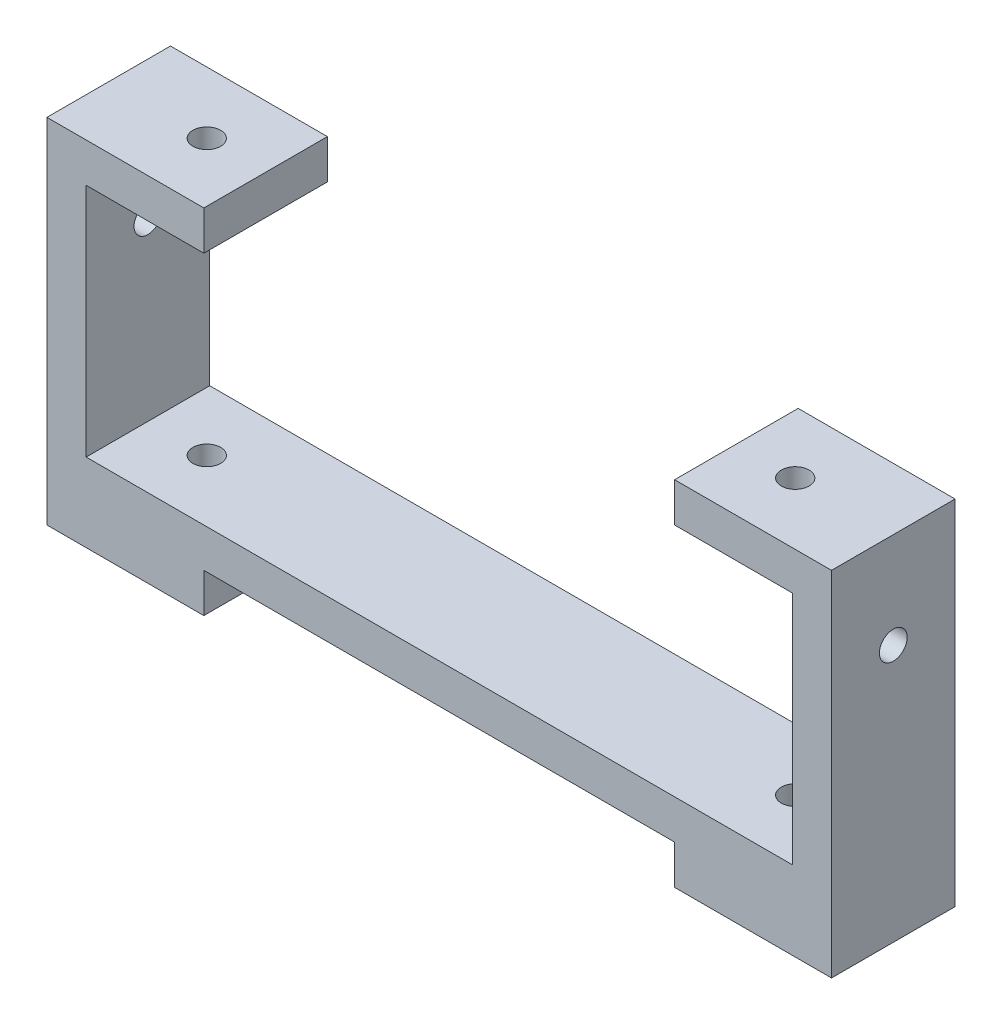
SolidWorks part; units mm, degrees
ref_plane "Front Plane" through (0, 0, 0) normal (0, 0, 1) x (1, 0, 0)
ref_plane "Top Plane" through (0, 0, 0) normal (0, 1, 0) x (1, 0, 0)
ref_plane "Right Plane" through (0, 0, 0) normal (1, 0, 0) x (0, 0, -1)
sketch "Sketch1" plane through (0, 0, 0) normal (0, 0, 1) x (1, 0, 0)
  line L0 (-57.15, -1.651) -> (-57.15, 36.449)
  line L1 (38.1, -8.001) -> (-38.1, -8.001)
  line L3 (-57.15, -1.651) -> (57.15, -1.651)
  line L7 (-57.15, 36.449) -> (-38.1, 36.449)
  line L8 (-38.1, 36.449) -> (-38.1, 42.799)
  line L9 (-38.1, 42.799) -> (-63.5, 42.799)
  line L10 (-63.5, 42.799) -> (-63.5, -3.175)
  line L12 (0, 0) -> (0, 14.3553) construction
  line L14 (63.5, 42.799) -> (63.5, -3.175)
  line L15 (38.1, 42.799) -> (63.5, 42.799)
  line L16 (38.1, 36.449) -> (38.1, 42.799)
  line L17 (57.15, 36.449) -> (38.1, 36.449)
  line L18 (57.15, -1.651) -> (57.15, 36.449)
  line L21 (-38.1, -8.001) -> (-38.1, -14.351)
  line L22 (-38.1, -14.351) -> (-63.5, -14.351)
  line L23 (-63.5, -14.351) -> (-63.5, -3.175)
  line L24 (38.1, -8.001) -> (38.1, -14.351)
  line L26 (38.1, -14.351) -> (63.5, -14.351)
  line L27 (63.5, -14.351) -> (63.5, -3.175)
  point P0 (0, 0)
  point P4 (0, 0)
  point P19 (-152.9342, -3.175)
  point P24 (-95.8112, -15.0439)
  point P26 (-39.0167, -7.1959)
  dimension "D1" = 6.35
  dimension "D2" = 6.35
  dimension "D3" = 6.35
  dimension "D4" = 6.35
  dimension "D5" = 127
  dimension "D6" = 25.4
  dimension "D8" = 19.05
  dimension "D10" = 57.15
extrude "Boss-Extrude1" add sketch "Sketch1" along normal mid plane 20
sketch "Sketch2" plane through (0, -1.651, 0) normal (0, 1, 0) x (1, 0, 0)
  line L0 (0, 0) -> (0, 41.8411) construction
  circle A0 centre (-47.625, 0) radius 2.25
  circle A1 centre (47.625, 0) radius 2.25
  dimension "D1" = 4.5
extrude "Cut-Extrude1" cut sketch "Sketch2" against normal up to next
sketch "Sketch3" plane through (-57.15, 0, 0) normal (1, 0, 0) x (0, 0, -1)
  line L1 (-10, 36.449) -> (10, 36.449) construction
  circle A1 centre (0, 26.797) radius 2.25
  dimension "D1" = 4.5
  dimension "D4" = 9.652
extrude "Cut-Extrude2" cut sketch "Sketch3" against normal up to next
sketch "Sketch4" plane through (0, 36.449, 0) normal (0, -1, 0) x (1, 0, 0)
  line L0 (0, 0) -> (0, 17.6311) construction
  circle A0 centre (-47.625, 0) radius 2.25
  circle A1 centre (47.625, 0) radius 2.25
  dimension "D1" = 4.5
extrude "Cut-Extrude3" cut sketch "Sketch4" against normal up to next
sketch "Sketch5" plane through (57.15, 0, 0) normal (-1, 0, 0) x (0, 0, 1)
  line L0 (10, 36.449) -> (-10, 36.449) construction
  circle A0 centre (0, 27.305) radius 2.25
  dimension "D1" = 4.5
  dimension "D3" = 9.144
extrude "Cut-Extrude4" cut sketch "Sketch5" against normal up to next
